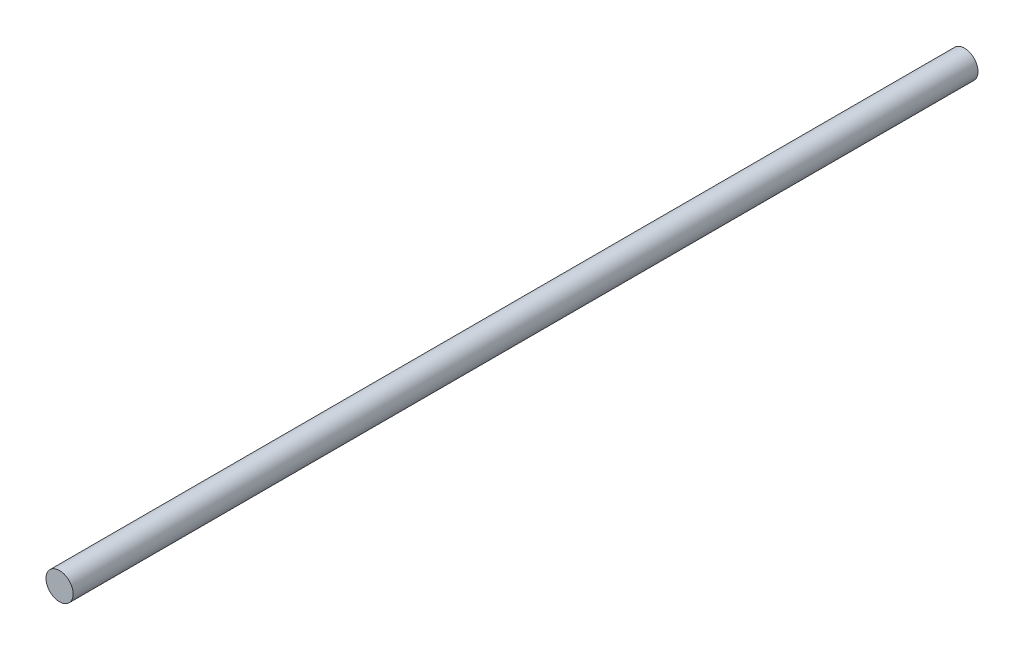
SolidWorks part; units mm, degrees
ref_plane "Front Plane" through (0, 0, 0) normal (0, 0, 1) x (1, 0, 0)
ref_plane "Top Plane" through (0, 0, 0) normal (0, 1, 0) x (1, 0, 0)
ref_plane "Right Plane" through (0, 0, 0) normal (1, 0, 0) x (0, 0, -1)
sketch "Sketch1" plane through (0, 0, 0) normal (0, 0, 1) x (1, 0, 0)
  circle A0 centre (0, 0) radius 4.7625
  dimension "D1" = 9.525
extrude "Boss-Extrude1" add sketch "Sketch1" against normal blind 317.5
